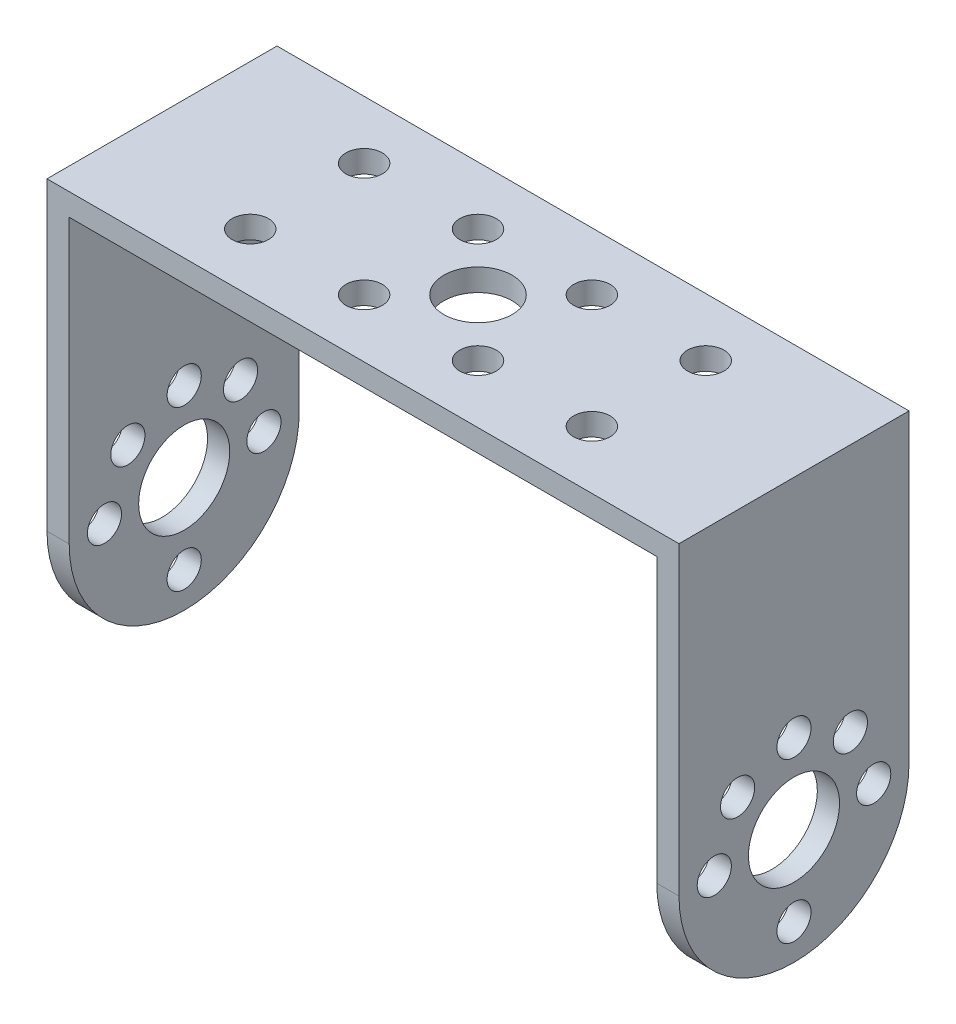
SolidWorks part; units mm, degrees
ref_plane "Plan de face" through (0, 0, 0) normal (0, 0, 1) x (1, 0, 0)
ref_plane "Plan de dessus" through (0, 0, 0) normal (0, 1, 0) x (1, 0, 0)
ref_plane "Plan de droite" through (0, 0, 0) normal (1, 0, 0) x (0, 0, -1)
sketch "Esquisse1" plane through (0, 0, 0) normal (0, 0, 1) x (1, 0, 0)
  line L0 (0, 0) -> (0, 36.9) construction
  line L1 (-27.75, 36.9) -> (27.75, 36.9)
  line L2 (27.75, 36.9) -> (27.75, 0)
  line L3 (27.75, 0) -> (25.8, 0)
  line L4 (25.8, 0) -> (25.8, 34.95)
  line L5 (25.8, 34.95) -> (-25.8, 34.95)
  line L6 (-25.8, 0) -> (-25.8, 34.95)
  line L7 (-27.75, 0) -> (-25.8, 0)
  line L8 (-27.75, 36.9) -> (-27.75, 0)
  point P9 (0, 34.95)
  dimension "D2" = 36.9
  dimension "D3" = 1.95
  dimension "D4" = 1.95
  dimension "D1" = 51.6
extrude "Boss.-Extru.1" add sketch "Esquisse1" along normal mid plane 20.2
sketch "Esquisse4" plane through (27.75, 0, 0) normal (1, 0, 0) x (0, 0, -1)
  line L0 (0, 0) -> (0, 10.1) construction
  line L1 (-10.1, 0) -> (-10.1, 36.9) construction
  line L3 (0, 10.1) -> (-10.1, 10.1) construction
  line L4 (-10.1, 10.1) -> (-10.1, 0)
  line L5 (-10.1, 0) -> (10.1, 0)
  line L9 (10.1, 10.1) -> (10.1, 0)
  arc A1 (-10.1, 10.1) -> (10.1, 10.1) centre (0, 10.1) ccw
  line M6 (10.1, 0) -> (10.1, 36.9)
  line M8 (-10.1, 36.9) -> (-10.1, 0)
  line M9 (-10.1, 0) -> (10.1, 0)
extrude "Enlèv. mat.-Extru.2" cut sketch "Esquisse4" against normal through all contours A1 M8 M9 | A1 L5 M6
sketch "Esquisse3" plane through (0, 36.9, 0) normal (0, 1, 0) x (1, 0, 0)
  line L0 (0, 10.1) -> (0, -10.1) construction
  line L1 (27.75, 10.1) -> (-27.75, 10.1) construction
  line L2 (27.75, -10.1) -> (-27.75, -10.1) construction
  line L3 (0, 0) -> (-27.75, 0) construction
  line L4 (-5, 5) -> (5, 5) construction
  line L5 (-5, 5) -> (-5, -5) construction
  line L6 (-5, -5) -> (5, -5) construction
  line L7 (5, 5) -> (5, -5) construction
  line L8 (-27.75, -10.1) -> (-27.75, 10.1) construction
  line L9 (-5, 5) -> (-15, 5) construction
  circle A0 centre (0, 0) radius 3
  circle A1 centre (0, 0) radius 7.0711 construction
  circle A2 centre (-5, 5) radius 1.6
  circle A3 centre (-5, -5) radius 1.6
  circle A4 centre (5, -5) radius 1.6
  circle A5 centre (5, 5) radius 1.6
  circle A6 centre (-15, 5) radius 1.6
  circle A7 centre (-15, -5) radius 1.6
  circle A8 centre (15, -5) radius 1.6
  circle A9 centre (15, 5) radius 1.6
  dimension "D1" = 6
  dimension "D2" = 3.2
  dimension "D3" = 10
  dimension "D4" = 30
extrude "Enlèv. mat.-Extru.1" cut sketch "Esquisse3" against normal through all
sketch "Esquisse5" plane through (27.75, 0, 0) normal (1, 0, 0) x (0, 0, -1)
  line L0 (-7, 10.1) -> (0, 10.1) construction
  line L1 (0, 10.1) -> (0, 17.1) construction
  line L2 (0, 17.1) -> (-7, 10.1) construction
  line L3 (0, 10.1) -> (-4.9497, 15.0497) construction
  line L4 (0, 10.1) -> (0, 3.1) construction
  circle A0 centre (0, 10.1) radius 4
  circle A1 centre (0, 10.1) radius 7 construction
  circle A2 centre (-7, 10.1) radius 1.5
  circle A3 centre (-4.9497, 15.0497) radius 1.5
  circle A4 centre (0, 17.1) radius 1.5
  circle A5 centre (0, 3.1) radius 1.5
  circle A6 centre (7, 10.1) radius 1.5
  circle A7 centre (4.9497, 15.0497) radius 1.5
  point P5 (-3.5, 13.6)
  dimension "D1" = 8
  dimension "D2" = 14
  dimension "D3" = 3
extrude "Enlèv. mat.-Extru.3" cut sketch "Esquisse5" against normal through all
equation "\"D4@Esquisse1\"=\"D3@Esquisse1\""
